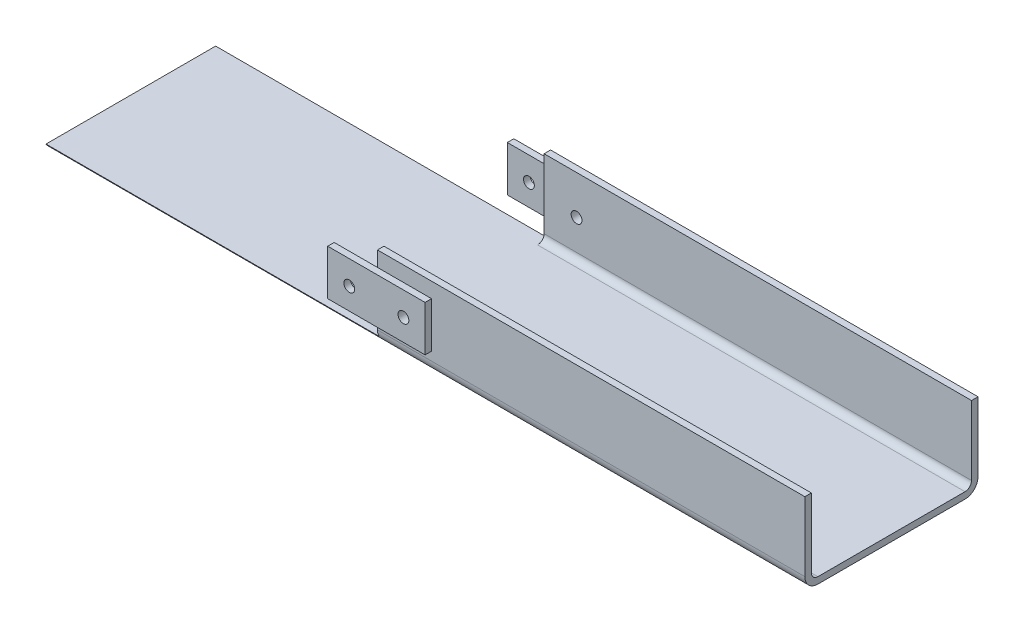
SolidWorks part; units mm, degrees
ref_plane "前视基准面" through (0, 0, 0) normal (0, 0, 1) x (1, 0, 0)
ref_plane "上视基准面" through (0, 0, 0) normal (0, 1, 0) x (1, 0, 0)
ref_plane "右视基准面" through (0, 0, 0) normal (1, 0, 0) x (0, 0, -1)
sketch "草图1" plane through (0, 0, 0) normal (0, 0, 1) x (1, 0, 0)
  line L0 (-103.1101, 0) -> (247.5, 0)
  line L1 (247.5, 0) -> (247.5, 3)
  line L2 (247.5, 3) -> (-103.963, 3)
  line L3 (-103.963, 3) -> (-103.1101, 0)
  point P4 (0, 0)
  dimension "D1" = 350.6101
  dimension "D2" = 351.463
  dimension "D3" = 3
  dimension "D4" = 247.5
extrude "Floor" add sketch "草图1" along normal mid plane 80
sketch "草图2" plane through (0, 0, 0) normal (0, 0, 1) x (1, 0, 0)
  line L0 (50, 3) -> (247.5, 3)
  line L1 (247.5, 3) -> (247.5, 38)
  line L2 (247.5, 38) -> (50, 38)
  line L3 (50, 38) -> (50, 3)
  point P4 (0, 0)
  dimension "D1" = 197.5
  dimension "D2" = 35
  dimension "D3" = 247.5
  dimension "D4" = 38
extrude "Side Front" add sketch "草图2" along normal blind 3 from offset 37
sketch "草图3" plane through (0, 0, 0) normal (0, 0, 1) x (1, 0, 0)
  line L0 (50, 3) -> (247.5, 3)
  line L1 (247.5, 3) -> (247.5, 38)
  line L2 (247.5, 38) -> (50, 38)
  line L3 (50, 38) -> (50, 3)
  point P4 (0, 0)
  dimension "D1" = 197.5
  dimension "D2" = 35
  dimension "D3" = 247.5
  dimension "D4" = 38
extrude "Side Rear" add sketch "草图3" against normal blind 3 from offset 37
fillet "Inside Bend Front" radius 3 1 edges at (148.75, 3, 37)
fillet "Inside Bend Rear" radius 3 1 edges at (148.75, 3, -37)
fillet "Outside Bend Front" radius 6 1 edges at (72.195, 0, 40)
fillet "Outside Bend Rear" radius 6 1 edges at (72.195, 0, -40)
sketch "草图4" plane through (0, 0, 0) normal (0, 0, 1) x (1, 0, 0)
  line L0 (30, 10) -> (75, 10)
  line L1 (75, 10) -> (75, 31)
  line L2 (75, 31) -> (30, 31)
  line L3 (30, 31) -> (30, 10)
extrude "Joint Front" add sketch "草图4" along normal blind 3 from offset 40
sketch "草图5" plane through (0, 0, 0) normal (0, 0, 1) x (1, 0, 0)
  line L0 (30, 10) -> (75, 10)
  line L1 (75, 10) -> (75, 31)
  line L2 (75, 31) -> (30, 31)
  line L3 (30, 31) -> (30, 10)
extrude "Joint Rear" add sketch "草图5" against normal blind 3 from offset 40
sketch "草图6" plane through (0, 0, 0) normal (0, 0, 1) x (1, 0, 0)
  circle A0 centre (40, 20) radius 2.5
  circle A1 centre (65, 20) radius 2.5
extrude "Fixing Holes" cut sketch "草图6" against normal mid plane 86
